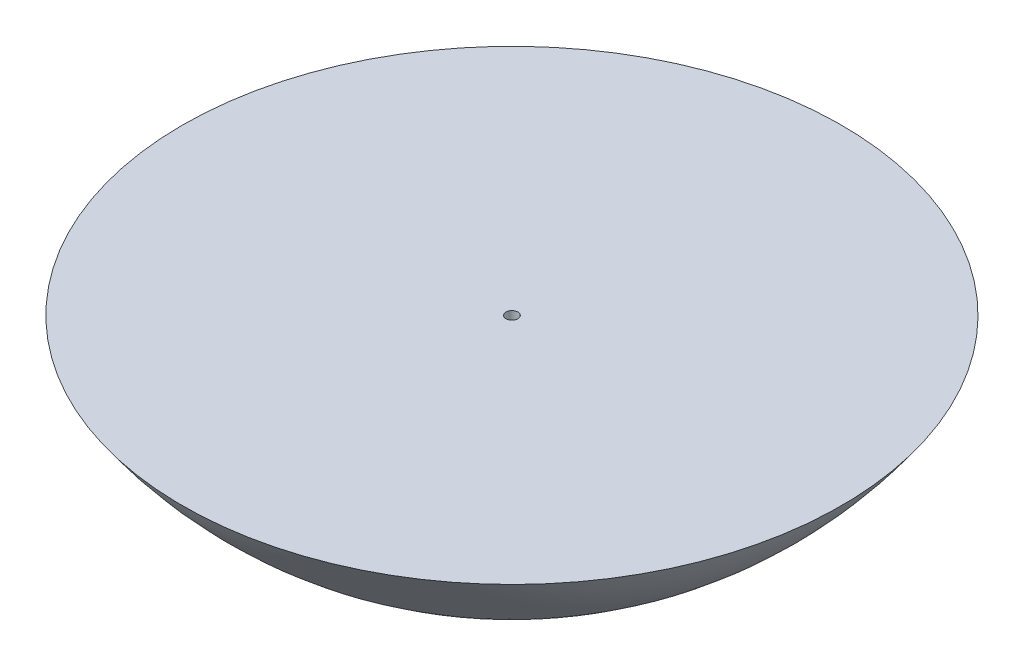
SolidWorks part; units mm, degrees
other "Markup1"
sketch "Sketch19" plane through (27.886, -16.1, -27.886) normal (0.7153, 0.5102, -0.4776) x (-0.4514, -0.1845, -0.8731)
ref_plane "Front Plane" through (0, 0, 0) normal (0, 0, 1) x (1, 0, 0)
ref_plane "Top Plane" through (0, 0, 0) normal (0, 1, 0) x (1, 0, 0)
ref_plane "Right Plane" through (0, 0, 0) normal (1, 0, 0) x (0, 0, -1)
sketch "Sketch1" plane through (0, 0, 0) normal (0, 0, 1) x (1, 0, 0)
  line L0 (0, -33.8) -> (0, 0)
  line L1 (33.8, 0) -> (0, 0)
  arc A0 (0, -33.8) -> (33.8, 0) centre (0, 0) ccw
  dimension "D1" = 33.8
revolve "Revolve1" add sketch "Sketch1" angle 360 about L0
sketch "Sketch2" plane through (0, 0, 0) normal (0, 1, 0) x (1, 0, 0)
  circle A0 centre (0, 0) radius 33.8 construction
  circle A1 centre (0, 0) radius 33.8
extrude "Cut-Extrude1" cut sketch "Sketch2" against normal blind 19.1
sketch "Sketch20" plane through (0, -19.1, 0) normal (0, 1, 0) x (1, 0, 0)
  circle A0 centre (0, 0) radius 0.5
  dimension "1.2" = 1
extrude "Cut-Extrude13" cut sketch "Sketch20" against normal through all
